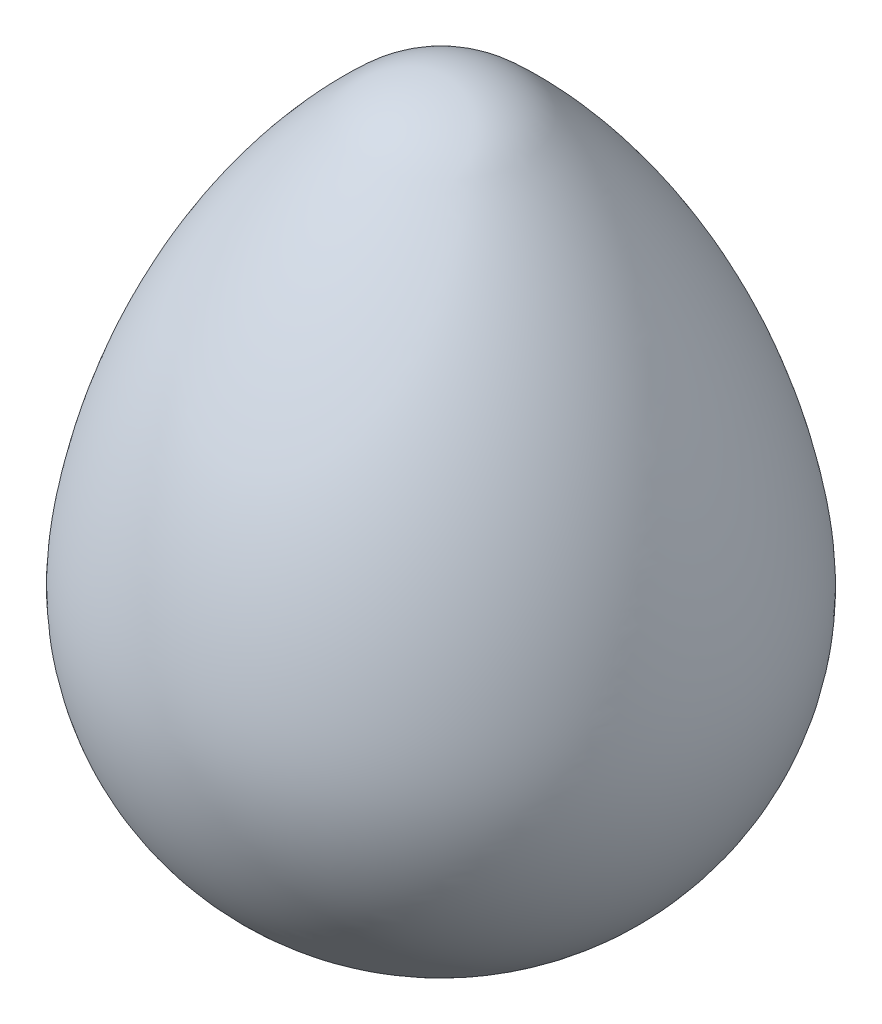
SolidWorks part; units mm, degrees
ref_plane "Front Plane" through (0, 0, 0) normal (0, 0, 1) x (1, 0, 0)
ref_plane "Top Plane" through (0, 0, 0) normal (0, 1, 0) x (1, 0, 0)
ref_plane "Right Plane" through (0, 0, 0) normal (1, 0, 0) x (0, 0, -1)
sketch "Sketch1" plane through (0, 0, 0) normal (0, 0, 1) x (1, 0, 0)
  line L15 (0, 27.5) -> (0, -17.5)
  line L16 (0, 0) -> (0, 35.011) construction
  arc A0 (0, -17.5) -> (17.2472, 2.9641) centre (0, 0) ccw construction
  arc A1 (17.2472, 2.9641) -> (5, 25.5408) centre (-22.1749, -3.8109) ccw construction
  arc A2 (5, 25.5408) -> (0, 27.5) centre (0, 20.1403) ccw construction
  spline S0 degree 3 poles (0, 27.5) (1.3925, 27.5) (2.7308, 27.115) (3.9105, 26.3751) (4.1686, 26.2133) (4.6647, 25.8575) (5.338, 25.229) (5.7755, 24.8049) (5.9919, 24.5903) (10.346, 20.2722) (13.6115, 15.0818) (15.6196, 9.2876) (16.1265, 7.8252) (16.9704, 4.8415) (17.7089, 0.0044) (17.2943, -3.0906) (16.8889, -4.5843) (14.7373, -12.5107) (8.2132, -17.5) (0, -17.5) knots 0 0 0 0 0.067726 0.067726 0.067726 0.082937 0.098149 0.11336 0.11336 0.11336 0.414275 0.414275 0.414275 0.491558 0.568841 0.646124 0.646124 0.646124 1 1 1 1 weights 1 0.97402 0.97402 1 1 1 1 1 1 0.982753 0.982753 1 1 1 1 1 1 0.862895 0.862895 1
  dimension "D1" = 35
  dimension "D2" = 45
  dimension "D4" = 40
  dimension "D3" = 10
revolve "Revolve1" add sketch "Sketch1" angle 360 about L16
